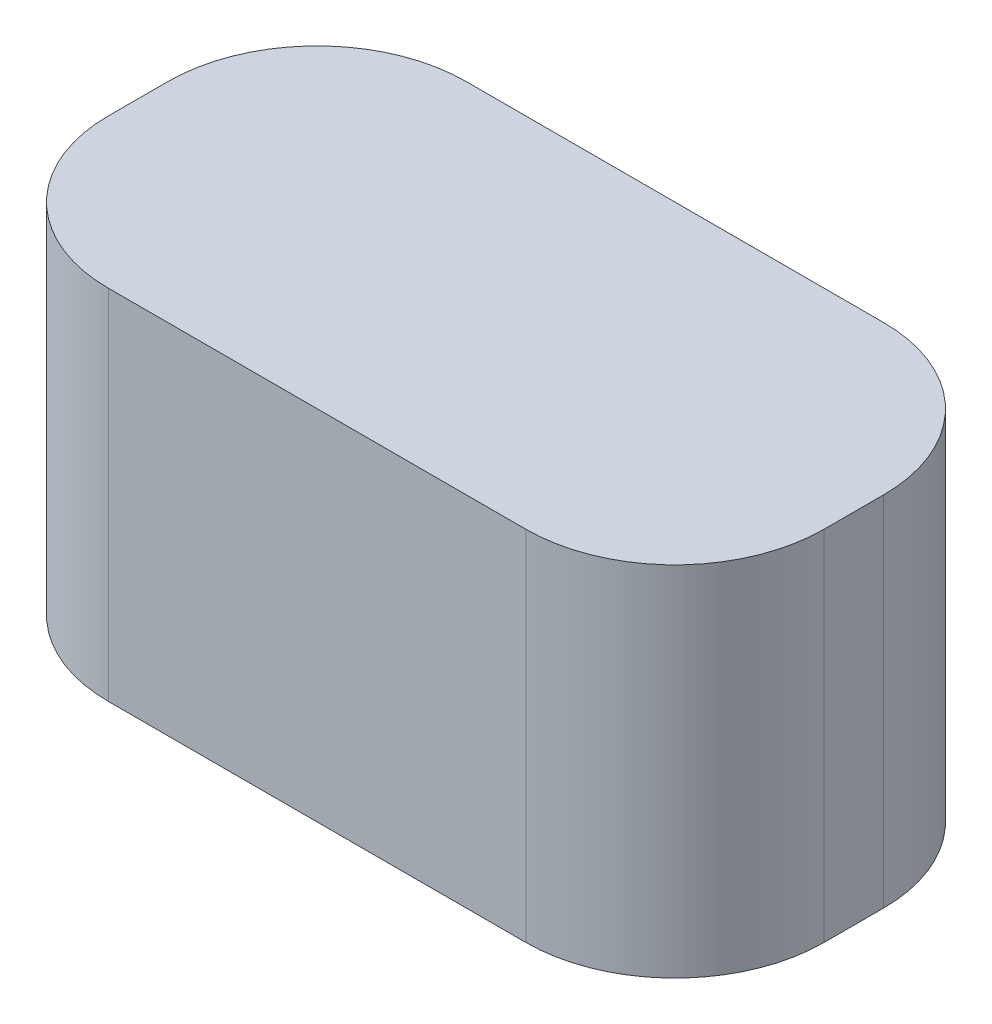
SolidWorks part; units mm, degrees
ref_plane "Plano frontal" through (0, 0, 0) normal (0, 0, 1) x (1, 0, 0)
ref_plane "Plano superior" through (0, 0, 0) normal (0, 1, 0) x (1, 0, 0)
ref_plane "Plano direito" through (0, 0, 0) normal (1, 0, 0) x (0, 0, -1)
sketch "Esboço1" plane through (0, 0, 0) normal (0, 1, 0) x (1, 0, 0)
  line L1 (-31.9215, -15.4038) -> (-17.9215, -15.4038)
  line L2 (-36.9215, -10.4038) -> (-36.9215, -8.4038)
  line L3 (-31.9215, -3.4038) -> (-17.9215, -3.4038)
  line L4 (-12.9215, -10.4038) -> (-12.9215, -8.4038)
  arc A0 (-17.9215, -15.4038) -> (-12.9215, -10.4038) centre (-17.9215, -10.4038) ccw
  arc A1 (-17.9215, -3.4038) -> (-12.9215, -8.4038) centre (-17.9215, -8.4038) cw
  arc A2 (-36.9215, -8.4038) -> (-31.9215, -3.4038) centre (-31.9215, -8.4038) cw
  arc A3 (-31.9215, -15.4038) -> (-36.9215, -10.4038) centre (-31.9215, -10.4038) cw
  point P6 (-12.9215, -15.4038)
  point P9 (-12.9215, -3.4038)
  point P14 (-36.9215, -15.4038)
  dimension "D3" = 5
  dimension "D1" = 12
  dimension "D2" = 24
extrude "Ressalto-extrusão1" add sketch "Esboço1" along normal blind 12
